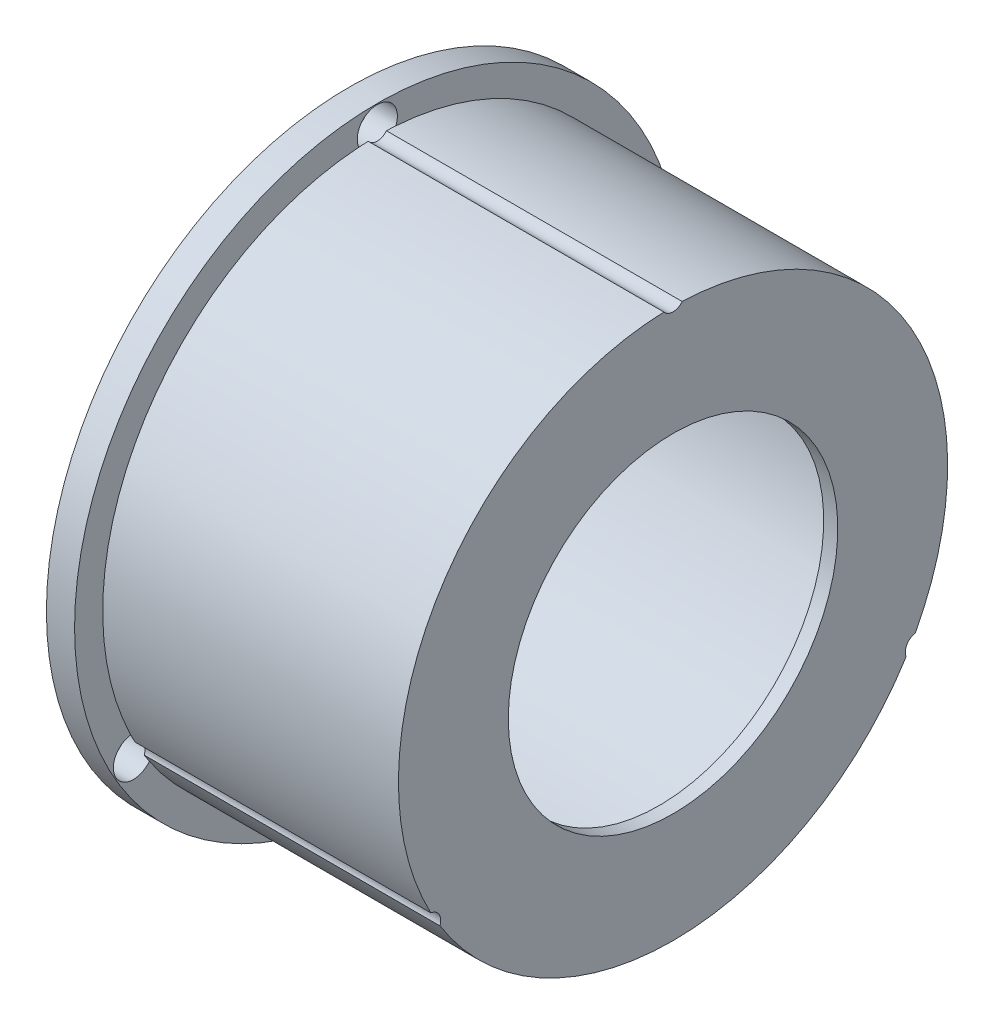
SolidWorks part; units mm, degrees
ref_plane "Front Plane" through (0, 0, 0) normal (0, 0, 1) x (1, 0, 0)
ref_plane "Top Plane" through (0, 0, 0) normal (0, 1, 0) x (1, 0, 0)
ref_plane "Right Plane" through (0, 0, 0) normal (1, 0, 0) x (0, 0, -1)
sketch "Axial profile (mm)" plane through (0, 0, 0) normal (0, 0, 1) x (1, 0, 0)
  line L0 (-110, 0) -> (75, 0) construction
  line L1 (135.7, 36.4) -> (179.7, 36.4)
  line L2 (179.7, 36.4) -> (179.7, 23.4)
  line L3 (179.7, 23.4) -> (181.7, 23.4)
  line L4 (181.7, 23.4) -> (181.7, 39)
  line L5 (181.7, 39) -> (139.7, 39)
  line L6 (139.7, 39) -> (139.7, 43)
  line L7 (139.7, 43) -> (135.7, 43)
  line L8 (135.7, 43) -> (135.7, 36.4)
revolve "Full revolution" add sketch "Axial profile (mm)" angle 360 about L0
sketch "Sketch2" plane through (0, 0, 0) normal (1, 0, 0) x (0, 0, -1)
  circle A0 centre (0, 40) radius 1.65
  circle A1 centre (-34.641, -20) radius 1.65
  circle A2 centre (34.641, -20) radius 1.65
extrude "Axial holes" cut sketch "Sketch2" along normal through all and the other way through all
sketch "Sketch3" plane through (0, 0, 0) normal (1, 0, 0) x (0, 0, -1)
  circle A0 centre (0, 40) radius 2.85
  circle A1 centre (-34.641, -20) radius 2.85
  circle A2 centre (34.641, -20) radius 2.85
extrude "Cut-Extrude2" cut sketch "Sketch3" along normal blind 4 from offset 135.7
